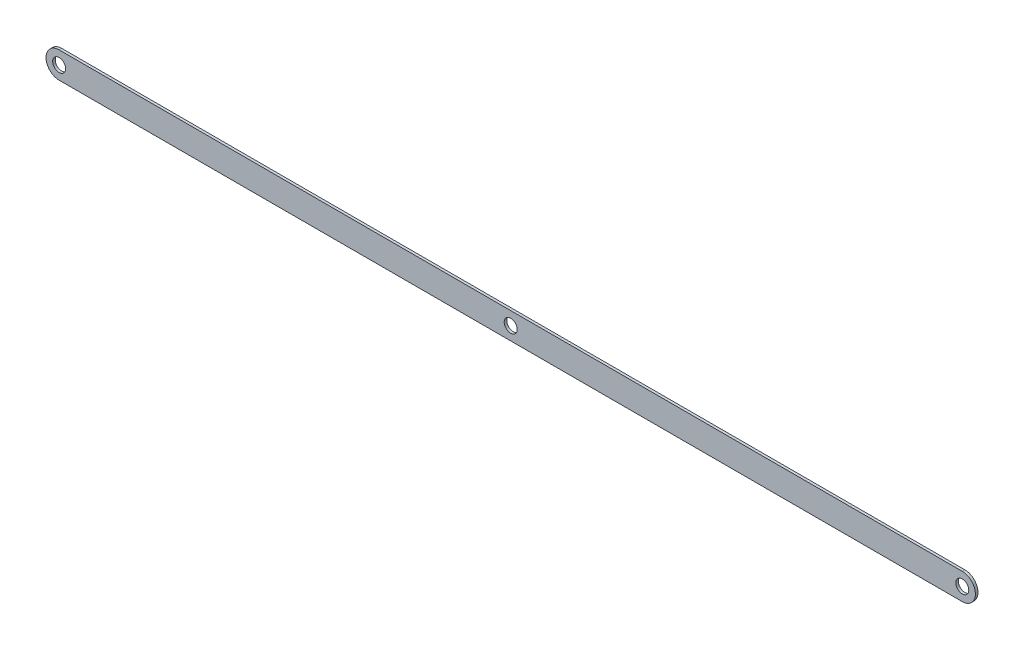
SolidWorks part; units mm, degrees
ref_plane "Front Plane" through (0, 0, 0) normal (0, 0, 1) x (1, 0, 0)
ref_plane "Top Plane" through (0, 0, 0) normal (0, 1, 0) x (1, 0, 0)
ref_plane "Right Plane" through (0, 0, 0) normal (1, 0, 0) x (0, 0, -1)
sketch "Sketch1" plane through (0, 0, 0) normal (0, 0, 1) x (1, 0, 0)
  line L0 (-1738.65, 0) -> (1738.65, 0) construction
  line L1 (-1738.65, 50.59) -> (1738.65, 50.59)
  line L2 (-1738.65, -50.59) -> (1738.65, -50.59)
  arc A0 (-1738.65, 50.59) -> (-1738.65, -50.59) centre (-1738.65, 0) ccw
  arc A1 (1738.65, -50.59) -> (1738.65, 50.59) centre (1738.65, 0) ccw
  point P2 (0, 0)
  dimension "D1" = 3477.3
extrude "Boss-Extrude1" add sketch "Sketch1" along normal blind 10
sketch "Sketch2" plane through (0, 0, 10) normal (0, 0, 1) x (1, 0, 0)
  circle A0 centre (0, 0) radius 25
  circle A1 centre (-1738.65, 0) radius 25
  circle A2 centre (1738.65, 0) radius 25
  dimension "D1" = 50
  dimension "D2" = 50
  dimension "D3" = 50
extrude "Cut-Extrude1" cut sketch "Sketch2" against normal blind 10
